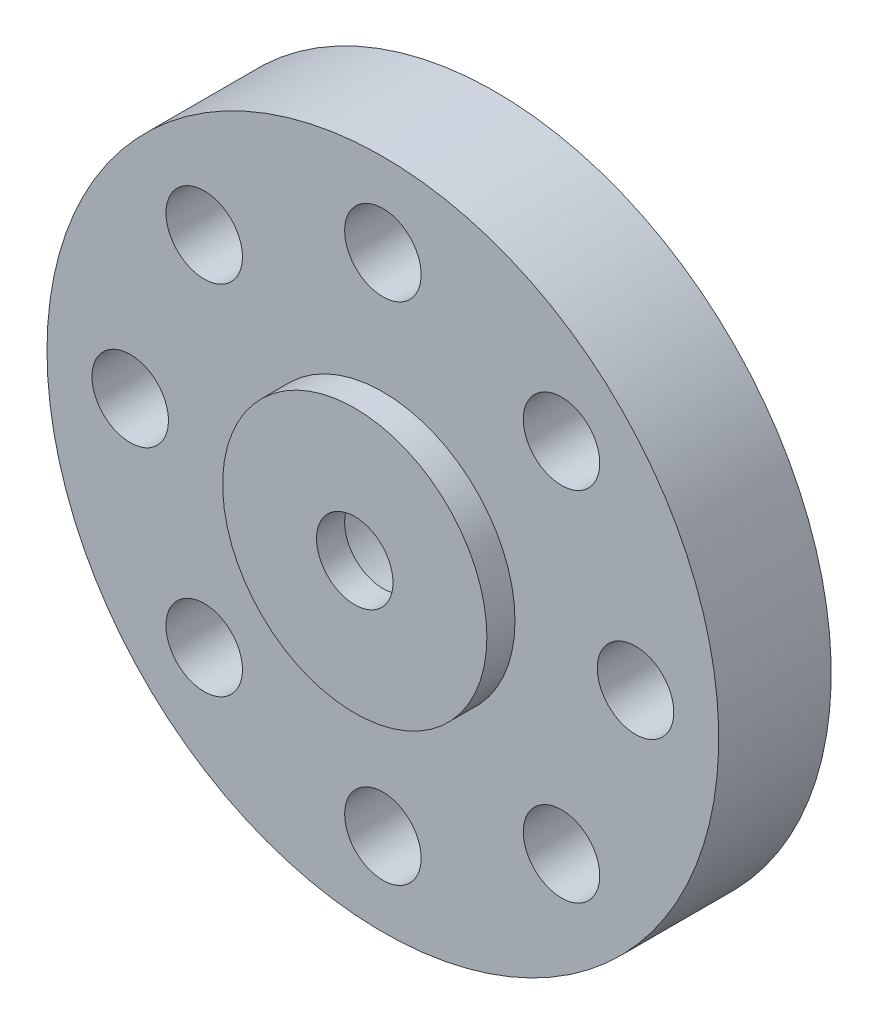
SolidWorks part; units mm, degrees
ref_plane "Front Plane" through (0, 0, 0) normal (0, 0, 1) x (1, 0, 0)
ref_plane "Top Plane" through (0, 0, 0) normal (0, 1, 0) x (1, 0, 0)
ref_plane "Right Plane" through (0, 0, 0) normal (1, 0, 0) x (0, 0, -1)
sketch "Sketch1" plane through (0, 0, 0) normal (0, 0, 1) x (1, 0, 0)
  circle A0 centre (19.5, 0) radius 5.875
  circle A1 centre (19.5, 0) radius 1.7
extrude "Boss-Extrude1" add sketch "Sketch1" against normal blind 1.25
sketch "Sketch2" plane through (0, 0, -1.25) normal (0, 0, -1) x (-1, 0, 0)
  circle A0 centre (-19.5, 0) radius 14.935
  circle A1 centre (-19.5, -11.235) radius 1.7
  circle A5 centre (-19.5, 0) radius 3.22
  circle A6 centre (-27.4443, -7.9443) radius 1.7
  circle A7 centre (-30.735, 0) radius 1.7
  circle A8 centre (-27.4443, 7.9443) radius 1.7
  circle A9 centre (-19.5, 11.235) radius 1.7
  circle A10 centre (-11.5557, 7.9443) radius 1.7
  circle A11 centre (-8.265, 0) radius 1.7
  circle A12 centre (-11.5557, -7.9443) radius 1.7
  point P14 (-19.5, 0)
  point P24 (-19.5, 0)
  dimension "D1" = 8
extrude "Boss-Extrude2" add sketch "Sketch2" along normal blind 5
